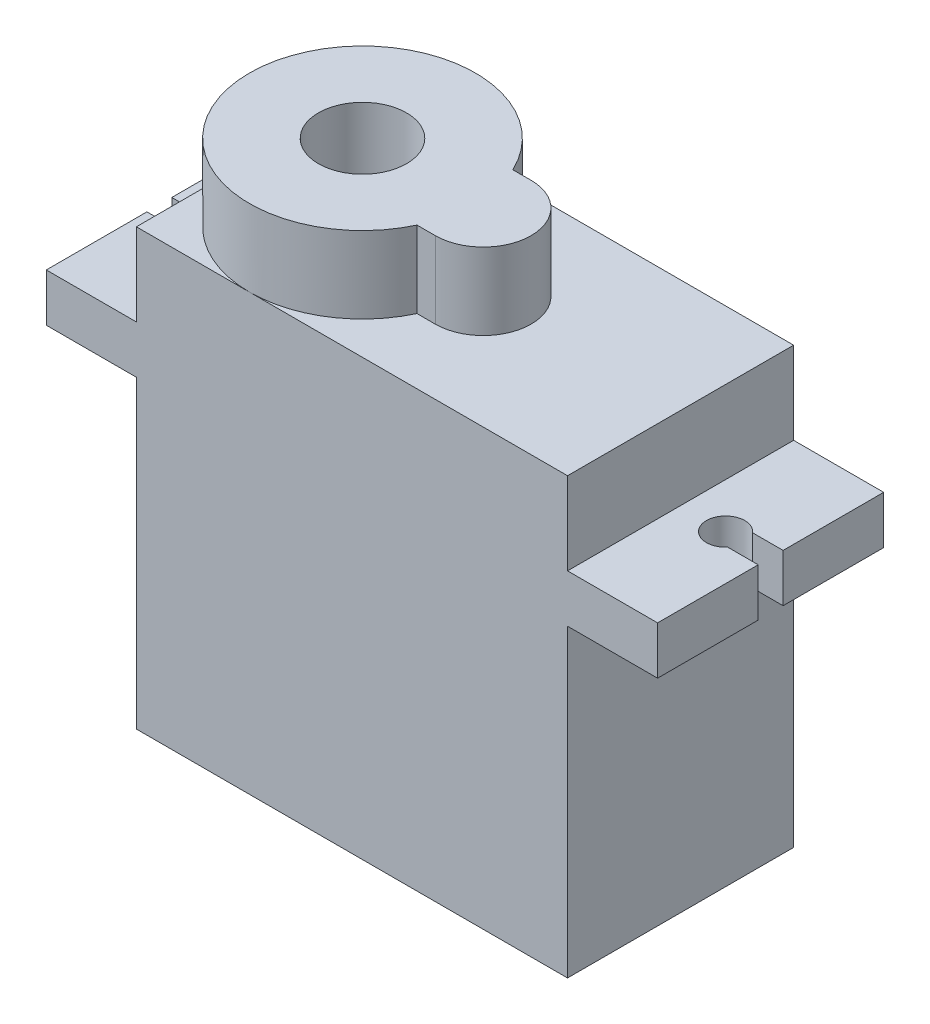
SolidWorks part; units mm, degrees
ref_plane "Ön Düzlem" through (0, 0, 0) normal (0, 0, 1) x (1, 0, 0)
ref_plane "Üst Düzlem" through (0, 0, 0) normal (0, 1, 0) x (1, 0, 0)
ref_plane "Sağ Düzlem" through (0, 0, 0) normal (1, 0, 0) x (0, 0, -1)
sketch "Sketch1" plane through (0, 0, 0) normal (0, 0, 1) x (1, 0, 0)
  line L1 (0, 0) -> (22.5, 0)
  line L2 (0, 0) -> (0, 15.9)
  line L3 (0, 22.7) -> (22.5, 22.7)
  line L4 (22.5, 0) -> (22.5, 15.9)
  line L5 (-4.7, 15.9) -> (0, 15.9)
  line L6 (-4.7, 18.4) -> (0, 18.4)
  line L7 (-4.7, 15.9) -> (-4.7, 18.4)
  line L8 (27.2, 15.9) -> (27.2, 18.4)
  line L9 (22.5, 15.9) -> (27.2, 15.9)
  line L10 (-4.7, 15.9) -> (27.2, 15.9) construction
  line L11 (22.5, 18.4) -> (27.2, 18.4)
  line L12 (-4.7, 18.4) -> (27.2, 18.4) construction
  line L13 (22.5, 18.4) -> (22.5, 22.7)
  line L14 (0, 18.4) -> (0, 22.7)
  dimension "D1" = 22.5
  dimension "D2" = 22.7
  dimension "D3" = 15.9
  dimension "D4" = 31.9
  dimension "D5" = 2.5
extrude "Boss-Extrude1" add sketch "Sketch1" along normal blind 11.8
sketch "Sketch2" plane through (0, 22.7, 0) normal (0, 1, 0) x (1, 0, 0)
  line L0 (0, -5.9) -> (5.9, -5.9) construction
  line L1 (0, -11.8) -> (0, 0) construction
  line L2 (5.9, -5.9) -> (14.7, -5.9) construction
  line L3 (12.2, -3.4) -> (11.2442, -3.4)
  line L4 (12.2, -8.4) -> (11.2442, -8.4)
  arc A0 (11.2442, -3.4) -> (11.2442, -8.4) centre (5.9, -5.9) ccw
  arc A3 (12.2, -8.4) -> (12.2, -3.4) centre (12.2, -5.9) ccw
  dimension "D2" = 8.8
  dimension "D3" = 2.5
  dimension "D1" = 5.9
extrude "Boss-Extrude2" add sketch "Sketch2" along normal blind 4
sketch "Sketch3" plane through (0, 26.7, 0) normal (0, 1, 0) x (1, 0, 0)
  circle A0 centre (5.9, -5.9) radius 2.3
  dimension "D1" = 4.6
extrude "Cut-Extrude1" cut sketch "Sketch3" against normal blind 4
sketch "Sketch4" plane through (0, 18.4, 0) normal (0, 1, 0) x (1, 0, 0)
  line L0 (-2.35, -5.9) -> (-2.35, 0) construction
  line L1 (0, 0) -> (-4.7, 0) construction
  line L2 (-2.35, -5.9) -> (-4.7, -5.9) construction
  line L3 (-4.7, -11.8) -> (-4.7, 0) construction
  line L4 (-4.7, -5.25) -> (-4.7, -6.55)
  line L5 (-4.7, -6.55) -> (-3.1099, -6.55)
  line L6 (-4.7, -5.25) -> (-3.1099, -5.25)
  arc A0 (-3.1099, -6.55) -> (-3.1099, -5.25) centre (-2.35, -5.9) ccw
  point P11 (-4.7, -5.9)
  dimension "D1" = 2
  dimension "D2" = 1.3
extrude "Cut-Extrude2" cut sketch "Sketch4" against normal blind 4
ref_plane "Plane1" through (11.25, 0, 0) normal (1, 0, 0) x (0, 0, -1)
mirror "Mirror1" about plane through (11.25, 0, 0) normal (1, 0, 0) of "Cut-Extrude2"
